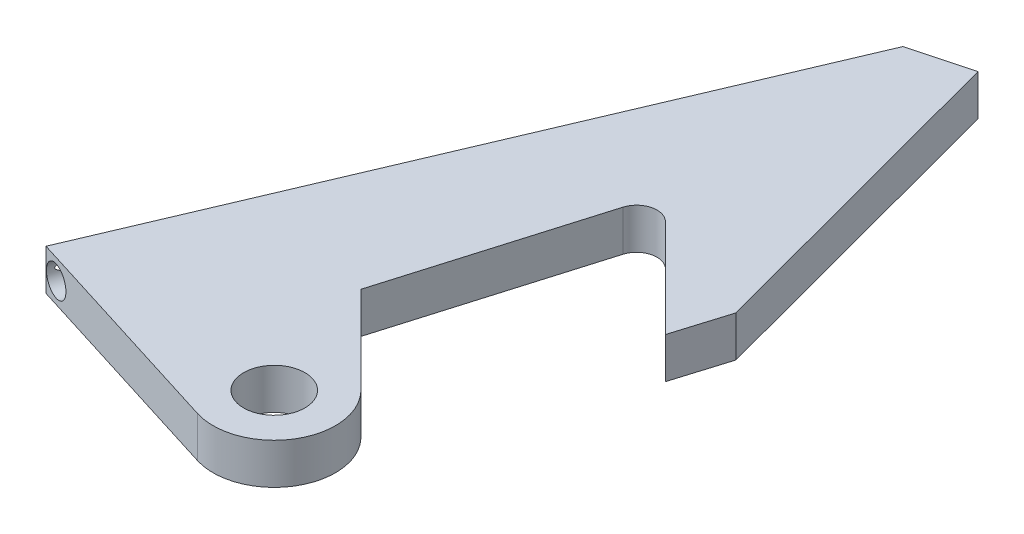
SolidWorks part; units mm, degrees
ref_plane "Front Plane" through (0, 0, 0) normal (0, 0, 1) x (1, 0, 0)
ref_plane "Top Plane" through (0, 0, 0) normal (0, 1, 0) x (1, 0, 0)
ref_plane "Right Plane" through (0, 0, 0) normal (1, 0, 0) x (0, 0, -1)
sketch "Sketch1" plane through (0, 0, 0) normal (0, 1, 0) x (1, 0, 0)
  line L14 (-2.7155, -50.4526) -> (-16.4492, -36.7162)
  line L15 (-0.2503, -64.2218) -> (8.9811, -34.0664) construction
  line L16 (-33.45, -172.6721) -> (154.2855, 440.5857) construction
  line L17 (-1.4647, -63.85) -> (7.7667, -33.6946) construction
  line L18 (-10.7741, -61.0002) -> (-1.5427, -30.8448) construction
  line L20 (-7.1439, -5.3021) -> (-16.4492, -36.7162)
  line L21 (13.3156, -19.1289) -> (-1.8546, -3.9587)
  line L24 (-12.3816, -66.1571) -> (-46.728, -55.3998)
  line L27 (15.8795, -10.7537) -> (2.2198, 40.5612)
  line L30 (-46.728, -55.3998) -> (-6.9942, 38.1085)
  line L31 (-6.9942, 38.1085) -> (2.2198, 40.5612)
  line L32 (13.3156, -19.1289) -> (15.8795, -10.7537)
  circle A4 centre (-9.5834, -57.0524) radius 4.7625
  arc A5 (-12.3816, -66.1571) -> (-2.7155, -50.4526) centre (-9.5834, -57.0524) ccw
  arc A8 (-1.8546, -3.9587) -> (-7.1439, -5.3021) centre (-4.0997, -6.2038) ccw
  circle A9 centre (-9.5834, -57.0524) radius 37.1814 construction
  point P27 (-5.6282, -0.1851)
  dimension "D2" = 38.1
  dimension "D1" = 1.27
  dimension "D3" = 74.3628
extrude "Boss-Extrude1" add sketch "Sketch1" along normal blind 6.35
sketch "Sketch2" plane through (-19.9756, 0, 63.7787) normal (-0.2989, 0, 0.9543) x (0.9543, 0, 0.2989)
  line L0 (-28.0339, 3.175) -> (-25.6209, 3.175) construction
  line L3 (-28.0339, 6.35) -> (-28.0339, 0) construction
hole_wizard "#14 (0.182) Diameter Hole1" positions "Sketch3" profile "Sketch4" hole size "#14" standard "ANSI Inch"
sketch "Sketch3" plane through (-19.9756, 0, 63.7787) normal (-0.2989, 0, 0.9543) x (0.9543, 0, 0.2989)
  point P0 (-25.6209, 3.175)
sketch "Sketch4" plane through (-44.4253, 3.175, 56.121) normal (0, 1, 0) x (0.9543, 0, 0.2989)
  line L0 (0, 0) -> (0, 3.9288)
  line L1 (0, 3.9288) -> (2.3114, 2.54)
  line L2 (2.3114, 2.54) -> (2.3114, 0)
  line L5 (2.3114, 0) -> (0, 0)
  line L10 (0, 3.9288) -> (-2.3114, 2.54) construction
  line L11 (0, -6.35) -> (0, 107.95) construction
  dimension "Hole Dia." = 4.6228
  dimension "Hole Depth" = 2.54
  dimension "Drill Angle" = 118
